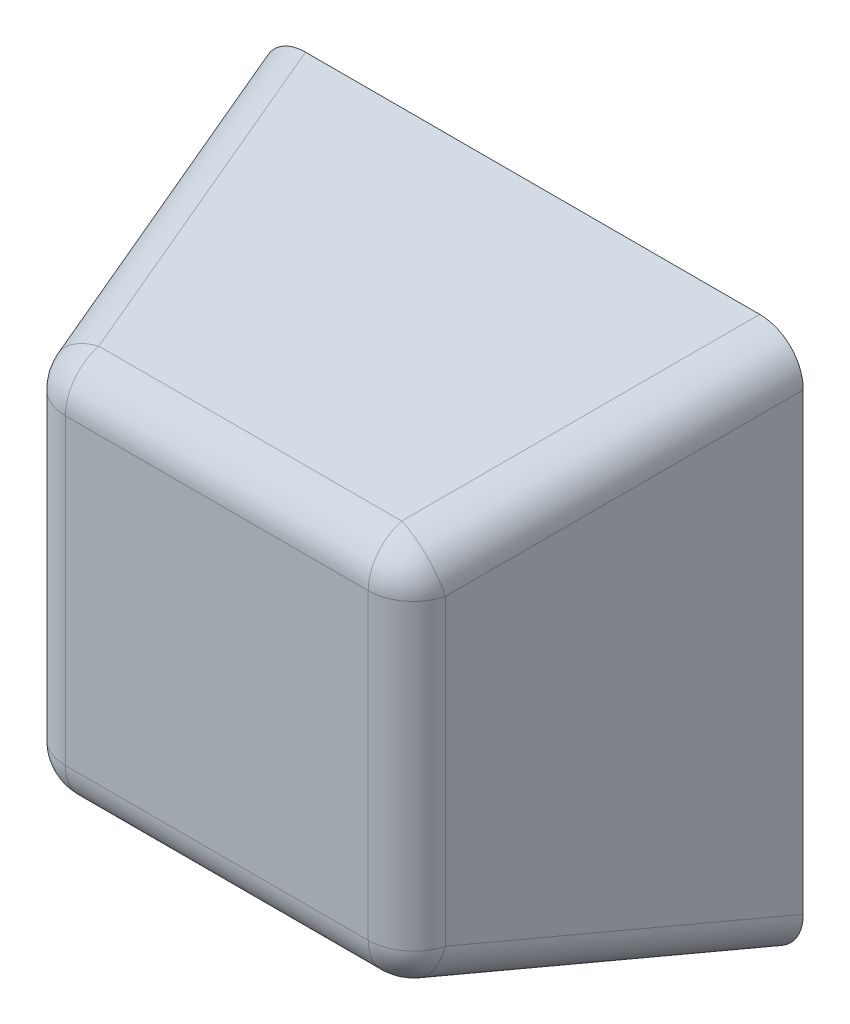
SolidWorks part; units mm, degrees
ref_plane "Front Plane" through (0, 0, 0) normal (0, 0, 1) x (1, 0, 0)
ref_plane "Top Plane" through (0, 0, 0) normal (0, 1, 0) x (1, 0, 0)
ref_plane "Right Plane" through (0, 0, 0) normal (1, 0, 0) x (0, 0, -1)
sketch "Sketch1" plane through (0, 0, 0) normal (0, 0, 1) x (1, 0, 0)
  line L1 (0, 0) -> (12, 0)
  line L2 (0, 0) -> (0, 12)
  line L3 (0, 12) -> (12, 12)
  line L4 (12, 0) -> (12, 12)
  dimension "D1" = 12
  dimension "D2" = 12
extrude "Boss-Extrude1" add sketch "Sketch1" along normal blind 7 draft 15
fillet "Fillet1" radius 1 8 edges at (6, 10.1244, 7) (10.1244, 6, 7) (6, 1.8756, 7) (1.8756, 6, 7) (0.9378, 0.9378, 3.5) (0.9378, 11.0622, 3.5) (11.0622, 11.0622, 3.5) (11.0622, 0.9378, 3.5)
